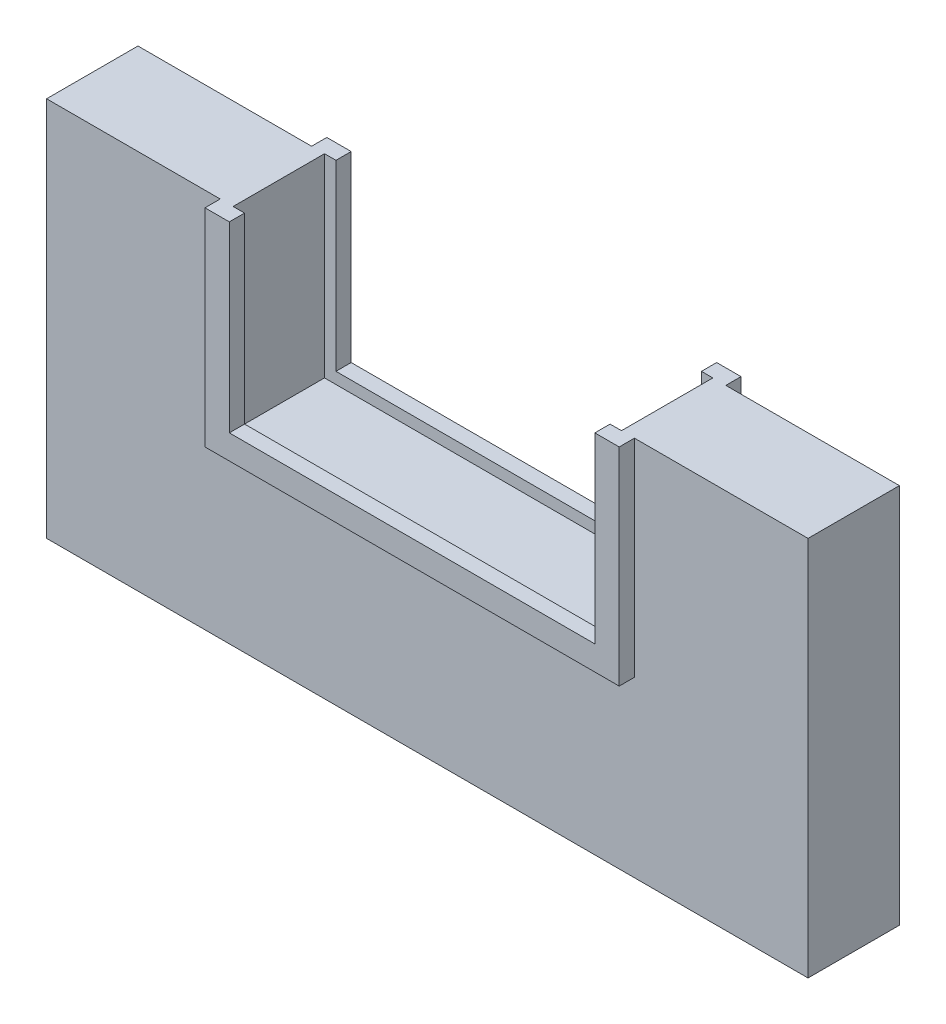
SolidWorks part; units mm, degrees
ref_plane "Front Plane" through (0, 0, 0) normal (0, 0, 1) x (1, 0, 0)
ref_plane "Top Plane" through (0, 0, 0) normal (0, 1, 0) x (1, 0, 0)
ref_plane "Right Plane" through (0, 0, 0) normal (1, 0, 0) x (0, 0, -1)
sketch "Sketch1" plane through (0, 0, 0) normal (0, 0, 1) x (1, 0, 0)
  line L1 (12.5, -6.25) -> (-12.5, -6.25)
  line L2 (12.5, -6.25) -> (12.5, 6.25)
  line L3 (12.5, 6.25) -> (-12.5, 6.25)
  line L4 (-12.5, -6.25) -> (-12.5, 6.25)
  line L5 (12.5, -6.25) -> (-12.5, 6.25) construction
  line L6 (12.5, 6.25) -> (-12.5, -6.25) construction
  point P0 (0, 0)
  dimension "D1" = 25
  dimension "D2" = 12.5
extrude "Boss-Extrude1" add sketch "Sketch1" along normal blind 3
sketch "Sketch2" plane through (0, 0, 3) normal (0, 0, 1) x (1, 0, 0)
  line L0 (12.5, 6.25) -> (-12.5, 6.25) construction
  line L1 (-6.8, 6.25) -> (6.8, 6.25)
  line L2 (-6.8, 6.25) -> (-6.8, -0.55)
  line L3 (-6.8, -0.55) -> (6.8, -0.55)
  line L4 (6.8, 6.25) -> (6.8, -0.55)
  line L5 (-12.5, 6.25) -> (-12.5, -6.25) construction
  line L6 (12.5, -6.25) -> (12.5, 6.25) construction
  line L7 (-12.5, -6.25) -> (12.5, -6.25) construction
  dimension "D1" = 5.7
  dimension "D2" = 5.7
  dimension "D3" = 5.7
extrude "Boss-Extrude3" add sketch "Sketch2" along normal mid plane 4 from offset 1.5 offset against normal yes
sketch "Sketch4" plane through (0, 0, 3.5) normal (0, 0, 1) x (1, 0, 0)
  line L0 (6.8, 6.25) -> (-6.8, 6.25) construction
  line L1 (-6.375, 6.25) -> (6.375, 6.25)
  line L2 (-6.375, 6.25) -> (-6.375, -0.125)
  line L3 (-6.375, -0.125) -> (6.375, -0.125)
  line L4 (6.375, 6.25) -> (6.375, -0.125)
  line L5 (-12.5, 6.25) -> (-12.5, -6.25) construction
  line L6 (12.5, -6.25) -> (12.5, 6.25) construction
  line L7 (-12.5, -6.25) -> (12.5, -6.25) construction
  dimension "D1" = 6.125
  dimension "D2" = 6.125
  dimension "D3" = 6.125
extrude "Cut-Extrude2" cut sketch "Sketch4" against normal mid plane 3 from offset 2 offset against normal yes
sketch "Sketch5" plane through (0, 0, 3.5) normal (0, 0, 1) x (1, 0, 0)
  line L0 (6.8, 6.25) -> (-6.8, 6.25) construction
  line L1 (-6, 6.25) -> (6, 6.25)
  line L2 (-6, 6.25) -> (-6, 0.25)
  line L3 (-6, 0.25) -> (6, 0.25)
  line L4 (6, 6.25) -> (6, 0.25)
  line L5 (-6.8, 6.25) -> (-6.8, -0.55) construction
  line L6 (6.8, 6.25) -> (6.8, -0.55) construction
  line L7 (-6.8, -0.55) -> (6.8, -0.55) construction
  dimension "D1" = 0.8
  dimension "D2" = 0.8
  dimension "D3" = 0.8
extrude "Cut-Extrude3" cut sketch "Sketch5" against normal blind 5
